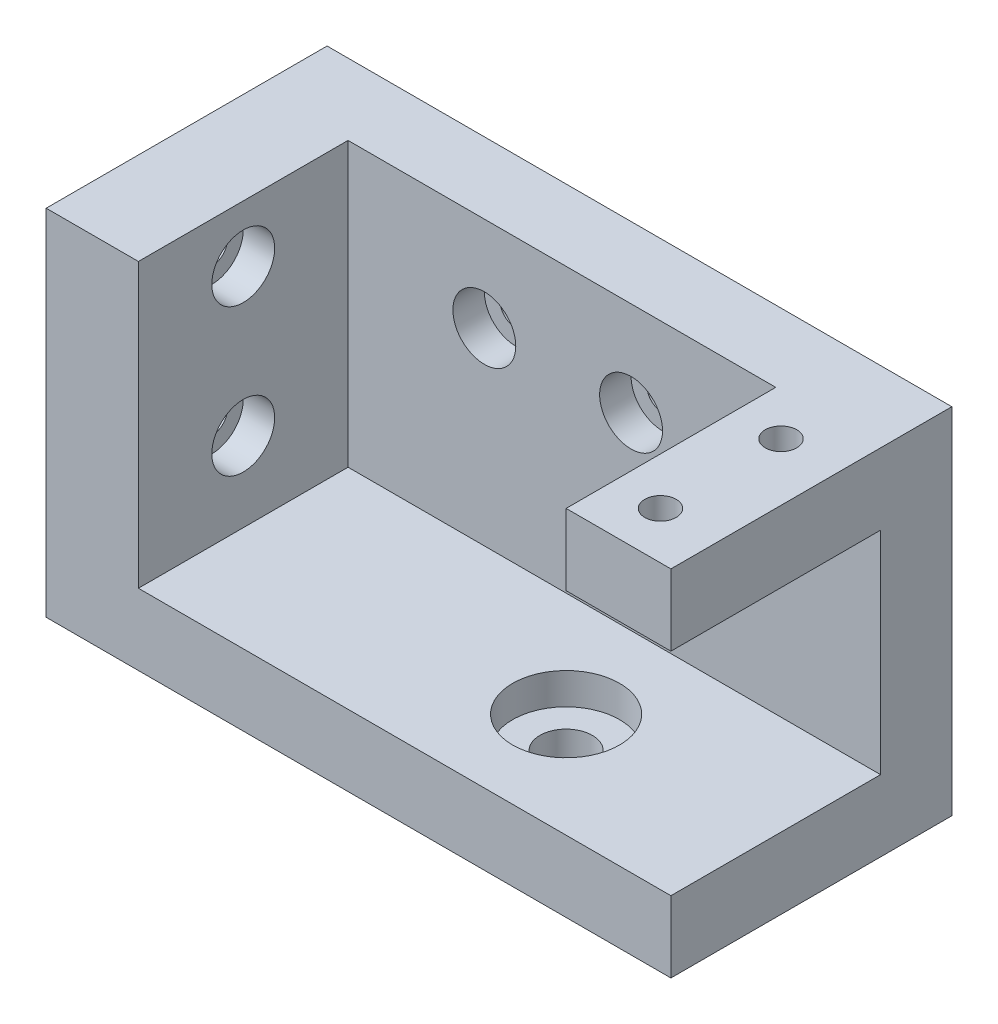
SolidWorks part; units mm, degrees
ref_plane "Front Plane" through (0, 0, 0) normal (0, 0, 1) x (1, 0, 0)
ref_plane "Top Plane" through (0, 0, 0) normal (0, 1, 0) x (1, 0, 0)
ref_plane "Right Plane" through (0, 0, 0) normal (1, 0, 0) x (0, 0, -1)
sketch "Sketch1" plane through (0, 0, 0) normal (0, 0, 1) x (1, 0, 0)
  line L1 (-13.0901, -4.8678) -> (27.7133, -4.8678)
  line L2 (-19.8901, -5.0178) -> (-19.8901, -11.8178)
  line L3 (-19.8901, -11.8178) -> (34.5133, -11.8178)
  line L4 (34.5133, -5.0178) -> (34.5133, -11.8178)
  line L5 (27.7133, 21.9822) -> (34.5133, 21.9822)
  line L6 (27.7133, 21.9822) -> (27.7133, -4.8678)
  line L8 (34.5133, 21.9822) -> (34.5133, -5.0178)
  line L10 (-19.8901, 21.9822) -> (-13.0901, 21.9822)
  line L11 (-19.8901, 21.9822) -> (-19.8901, -5.0178)
  line L13 (-13.0901, 21.9822) -> (-13.0901, -4.8678)
  dimension "D1" = 54.4034
  dimension "D2" = 33.8
  dimension "D3" = 6.8
  dimension "D4" = 27
  dimension "D5" = 6.8
  dimension "D6" = 27
  dimension "D7" = 40.8034
  dimension "D8" = 33.8
extrude "Boss-Extrude2" add sketch "Sketch1" along normal blind 20
sketch "Sketch4" plane through (-19.8901, 0, 0) normal (-1, 0, 0) x (0, 0, 1)
  line L1 (0, 21.9822) -> (-6.8, 21.9822)
  line L2 (0, 21.9822) -> (0, -11.8178)
  line L3 (0, -11.8178) -> (-6.8, -11.8178)
  line L4 (-6.8, 21.9822) -> (-6.8, -11.8178)
  dimension "D1" = 33.8
  dimension "D2" = 6.8
extrude "Boss-Extrude3" add sketch "Sketch4" against normal blind 53.6 contours L2 L1 L4 L3
sketch "Sketch8" plane through (34.5133, 0, 0) normal (1, 0, 0) x (0, 0, -1)
  line L0 (-20, -11.8178) -> (-20, 21.9822) construction
  line L1 (-20, 15.1822) -> (0, 15.1822)
  line L2 (-20, 15.1822) -> (-20, -5.0178)
  line L3 (-20, -5.0178) -> (0, -5.0178)
  line L4 (0, 15.1822) -> (0, -5.0178)
  line L5 (-20, 21.9822) -> (0, 21.9822) construction
  dimension "D1" = 20
  dimension "D2" = 6.8
  dimension "D3" = 6.8
extrude "Cut-Extrude1" cut sketch "Sketch8" against normal blind 53.6
sketch "Sketch9" plane through (0, -5.0178, 0) normal (0, 1, 0) x (1, 0, 0)
  line L0 (27.7133, 0) -> (-13.0901, 0) construction
  circle A0 centre (17.7133, -10) radius 2.5
  circle A1 centre (17.7133, -10) radius 5
  dimension "D1" = 10
  dimension "D2" = 10
extrude "Cut-Extrude3" cut sketch "Sketch9" against normal blind 3 contours A1 A0
sketch "Sketch11" plane through (0, -8.0178, 0) normal (0, 1, 0) x (1, 0, 0)
  circle A0 centre (17.7133, -10) radius 2.5
extrude "Cut-Extrude4" cut sketch "Sketch11" against normal blind 20
sketch "Sketch12" plane through (0, 21.9822, 0) normal (0, 1, 0) x (1, 0, 0)
  line L0 (34.5133, -20) -> (27.7133, -20) construction
  line L1 (34.5133, -20) -> (34.5133, 0) construction
  circle A0 centre (32.5133, -15.3) radius 1.1
  circle A1 centre (31.7099, -4.7) radius 1.1
  dimension "D3" = 4.7
  dimension "D1" = 4.7
  dimension "D2" = 2
  dimension "D4" = 2
extrude "Cut-Extrude6" cut sketch "Sketch12" against normal blind 20
sketch "Sketch13" plane through (0, 21.9822, 0) normal (0, 1, 0) x (1, 0, 0)
  line L1 (33.7099, 6.8) -> (35.7099, 6.8)
  line L2 (33.7099, 6.8) -> (33.7099, -20)
  line L3 (33.7099, -20) -> (35.7099, -20)
  line L4 (35.7099, 6.8) -> (35.7099, -20)
  dimension "D1" = 2
  dimension "D2" = 26.8
extrude "Boss-Extrude4" add sketch "Sketch13" against normal blind 33.8
sketch "Sketch16" plane through (0, 21.9822, 0) normal (0, 1, 0) x (1, 0, 0)
  line L0 (-13.0901, -20) -> (-19.8901, -20) construction
  circle A0 centre (-17.8901, -15.3) radius 1.1
  circle A1 centre (-17.8901, -4.7) radius 1.1
  dimension "D2" = 2
  dimension "D3" = 4.7
  dimension "D1" = 4.7
  dimension "D4" = 2
extrude "Cut-Extrude7" cut sketch "Sketch16" against normal blind 20
sketch "Sketch17" plane through (0, 21.9822, 0) normal (0, 1, 0) x (1, 0, 0)
  line L1 (-19.8901, 6.8) -> (-21.8901, 6.8)
  line L2 (-19.8901, 6.8) -> (-19.8901, -20)
  line L3 (-19.8901, -20) -> (-21.8901, -20)
  line L4 (-21.8901, 6.8) -> (-21.8901, -20)
  dimension "D1" = 2
  dimension "D2" = 26.8
extrude "Boss-Extrude5" add sketch "Sketch17" against normal blind 33.8
sketch "Sketch18" plane through (33.7099, 0, 0) normal (-1, 0, 0) x (0, 0, 1)
  line L1 (20, 15.1822) -> (0, 15.1822)
  line L2 (20, 15.1822) -> (20, -5.0178)
  line L3 (20, -5.0178) -> (0, -5.0178)
  line L4 (0, 15.1822) -> (0, -5.0178)
extrude "Cut-Extrude9" cut sketch "Sketch18" along normal blind 60
sketch "Sketch19" plane through (33.7099, 0, 0) normal (-1, 0, 0) x (0, 0, 1)
  line L0 (0, -5.0178) -> (0, 15.1822) construction
  line L1 (20, 15.1822) -> (0, 15.1822)
  line L2 (20, 15.1822) -> (20, -5.0178)
  line L3 (20, -5.0178) -> (0, -5.0178)
  line L4 (0, 15.1822) -> (0, -5.0178)
extrude "Cut-Extrude10" cut sketch "Sketch19" against normal blind 60
sketch "Sketch20" plane through (0, 0, 0) normal (0, 0, 1) x (1, 0, 0)
  line L0 (-21.8901, -5.0178) -> (35.7099, -5.0178) construction
  line L1 (-21.8901, 15.1822) -> (-13.0901, 15.1822)
  line L2 (-21.8901, 15.1822) -> (-21.8901, -5.0178)
  line L3 (-21.8901, -5.0178) -> (-13.0901, -5.0178)
  line L4 (-13.0901, 15.1822) -> (-13.0901, -5.0178)
  dimension "D1" = 8.8
extrude "Boss-Extrude6" add sketch "Sketch20" along normal blind 20
sketch "Sketch21" plane through (0, 21.9822, 0) normal (0, 1, 0) x (1, 0, 0)
  circle A0 centre (-17.8901, -4.7) radius 1.1
extrude "Boss-Extrude7" add sketch "Sketch21" against normal blind 13.6
sketch "Sketch23" plane through (0, 21.9822, 0) normal (0, 1, 0) x (1, 0, 0)
  circle A0 centre (-17.8901, -15.3) radius 1.1
extrude "Boss-Extrude8" add sketch "Sketch23" against normal blind 13.6
sketch "Sketch24" plane through (0, 21.9822, 0) normal (0, 1, 0) x (1, 0, 0)
  circle A0 centre (32.5133, -15.3) radius 1.1252
extrude "Boss-Extrude9" add sketch "Sketch24" against normal blind 6.8
sketch "Sketch25" plane through (0, 21.9822, 0) normal (0, 1, 0) x (1, 0, 0)
  circle A0 centre (29.7152, -15.1505) radius 1.1
  circle A1 centre (31.7099, -4.7) radius 1.4409
  dimension "D2" = 2.2
  dimension "D1" = 2.0019
extrude "Boss-Extrude10" add sketch "Sketch25" against normal blind 6.8
sketch "Sketch26" plane through (0, 21.9822, 0) normal (0, 1, 0) x (1, 0, 0)
  circle A0 centre (32.2133, -4.5) radius 1.5
  circle A1 centre (32.2133, -15.5) radius 1.5
  dimension "D5" = 3
  dimension "D6" = 3
  dimension "D1" = 4.5
  dimension "D2" = 4.5
  dimension "D3" = 4.5
  dimension "D4" = 4.5
extrude "Cut-Extrude11" cut sketch "Sketch26" against normal blind 10
sketch "Sketch27" plane through (0, 0, -6.8) normal (0, 0, -1) x (-1, 0, 0)
  circle A0 centre (-13.9099, 12.9822) radius 1.5
  circle A1 centre (0.0901, 12.9822) radius 1.5
  dimension "D5" = 3
  dimension "D6" = 3
  dimension "D1" = 9
  dimension "D2" = 9
  dimension "D3" = 21.8
  dimension "D4" = 14
  dimension "D7" = 13
  dimension "D8" = 21.8
extrude "Cut-Extrude12" cut sketch "Sketch27" against normal blind 10
sketch "Sketch29" plane through (-21.8901, 0, 0) normal (-1, 0, 0) x (0, 0, 1)
  circle A0 centre (10, 2.5822) radius 1.5
  circle A1 centre (10, 16.5822) radius 1.5
  dimension "D4" = 3
  dimension "D5" = 3
  dimension "D1" = 10
  dimension "D2" = 5.4
  dimension "D3" = 14
  dimension "D6" = 10
extrude "Cut-Extrude15" cut sketch "Sketch29" against normal blind 10
sketch "Sketch31" plane through (-13.0901, 0, 0) normal (1, 0, 0) x (0, 0, -1)
  circle A0 centre (-10, 2.5822) radius 3
  circle A1 centre (-10, 16.5822) radius 3
extrude "Cut-Extrude16" cut sketch "Sketch31" against normal blind 3
sketch "Sketch32" plane through (0, 0, 0) normal (0, 0, 1) x (1, 0, 0)
  circle A0 centre (-0.0901, 12.9822) radius 3
  circle A1 centre (13.9099, 12.9822) radius 3
extrude "Cut-Extrude17" cut sketch "Sketch32" against normal blind 3
sketch "Sketch33" plane through (0, -5.0178, 0) normal (0, 1, 0) x (1, 0, 0)
  circle A0 centre (17.7133, -10) radius 5.1
extrude "Cut-Extrude18" cut sketch "Sketch33" against normal blind 3
sketch "Sketch35" plane through (35.7099, 0, 0) normal (1, 0, 0) x (0, 0, -1)
  line L1 (-20, 15.1822) -> (6.8, 15.1822)
  line L2 (-20, 15.1822) -> (-20, 21.9822)
  line L3 (-20, 21.9822) -> (6.8, 21.9822)
  line L4 (6.8, 15.1822) -> (6.8, 21.9822)
  line L5 (-20, -5.0178) -> (6.8, -5.0178)
  line L6 (-20, -5.0178) -> (-20, -11.8178)
  line L7 (-20, -11.8178) -> (6.8, -11.8178)
  line L8 (6.8, -5.0178) -> (6.8, -11.8178)
  line L9 (6.8, 15.1822) -> (0, 15.1822)
  line L10 (6.8, 15.1822) -> (6.8, -5.0178)
  line L11 (6.8, -5.0178) -> (0, -5.0178)
  line L12 (0, 15.1822) -> (0, -5.0178)
  line M1 (0, -5.0178) -> (-20, -5.0178)
  line M2 (-20, -5.0178) -> (-20, -11.8178)
  line M3 (-20, -11.8178) -> (6.8, -11.8178)
  line M4 (6.8, -11.8178) -> (6.8, 21.9822)
  line M5 (6.8, 21.9822) -> (-20, 21.9822)
  line M6 (-20, 21.9822) -> (-20, 15.1822)
  line M7 (-20, 15.1822) -> (0, 15.1822)
  line M8 (0, 15.1822) -> (0, -5.0178)
extrude "Boss-Extrude11" add sketch "Sketch35" along normal blind 2 contours L1 M7 M4 M5 M6 | L5 L1 M8 M4 | L5 M1 M2 M3 M4
sketch "Sketch36" plane through (0, 21.9822, 0) normal (0, 1, 0) x (1, 0, 0)
  circle A0 centre (31.7133, -4) radius 2.5
  point P3 (0, 0)
  point P5 (0, 0)
  dimension "D3" = 5
  dimension "D1" = 4
  dimension "D2" = 4
extrude "Boss-Extrude13" add sketch "Sketch36" against normal blind 6.8
sketch "Sketch37" plane through (0, 21.9822, 0) normal (0, 1, 0) x (1, 0, 0)
  circle A0 centre (32.2133, -4) radius 1.5
  dimension "D2" = 3
  dimension "D1" = 4.5
  dimension "D3" = 4
extrude "Cut-Extrude19" cut sketch "Sketch37" against normal blind 6.8
